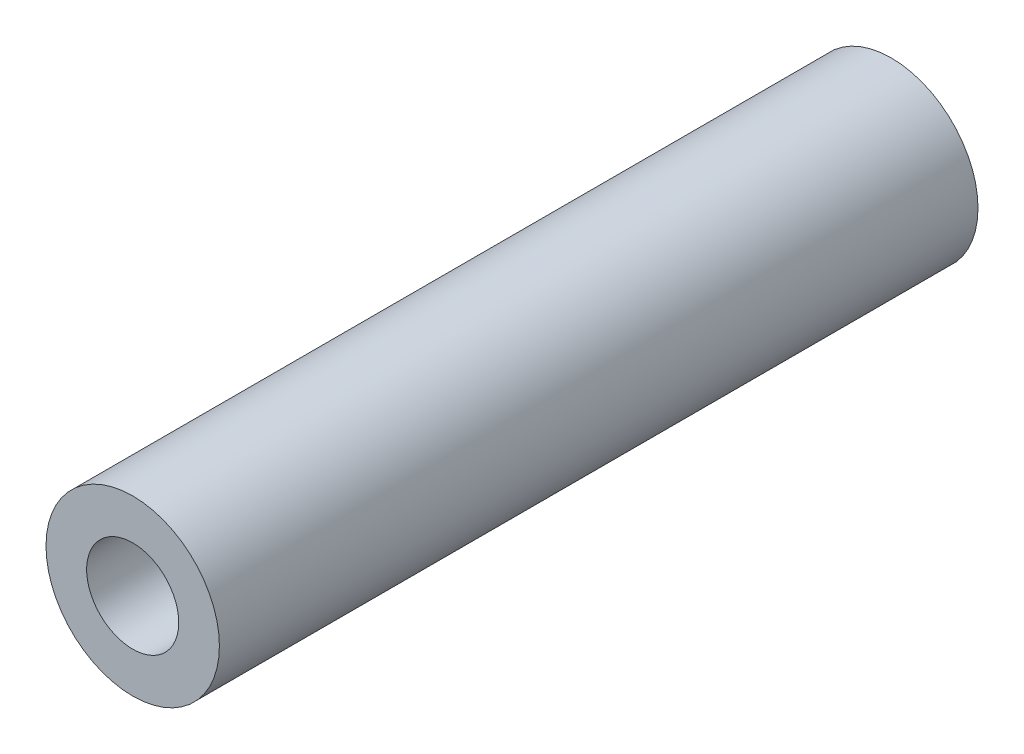
SolidWorks part; units mm, degrees
ref_plane "Front Plane" through (0, 0, 0) normal (0, 0, 1) x (1, 0, 0)
ref_plane "Top Plane" through (0, 0, 0) normal (0, 1, 0) x (1, 0, 0)
ref_plane "Right Plane" through (0, 0, 0) normal (1, 0, 0) x (0, 0, -1)
sketch "Sketch1" plane through (0, 0, 0) normal (0, 0, 1) x (1, 0, 0)
  circle A0 centre (0, 0) radius 8
extrude "16 mm moving rod representation" add sketch "Sketch1" along normal blind 70
sketch "Sketch2" plane through (0, 0, 0) normal (0, 0, 1) x (1, 0, 0)
  circle A0 centre (0, 0) radius 4.25
extrude "M10 x 1.5 female thread core - 12 mm depth" cut sketch "Sketch2" along normal blind 12 from offset 58
